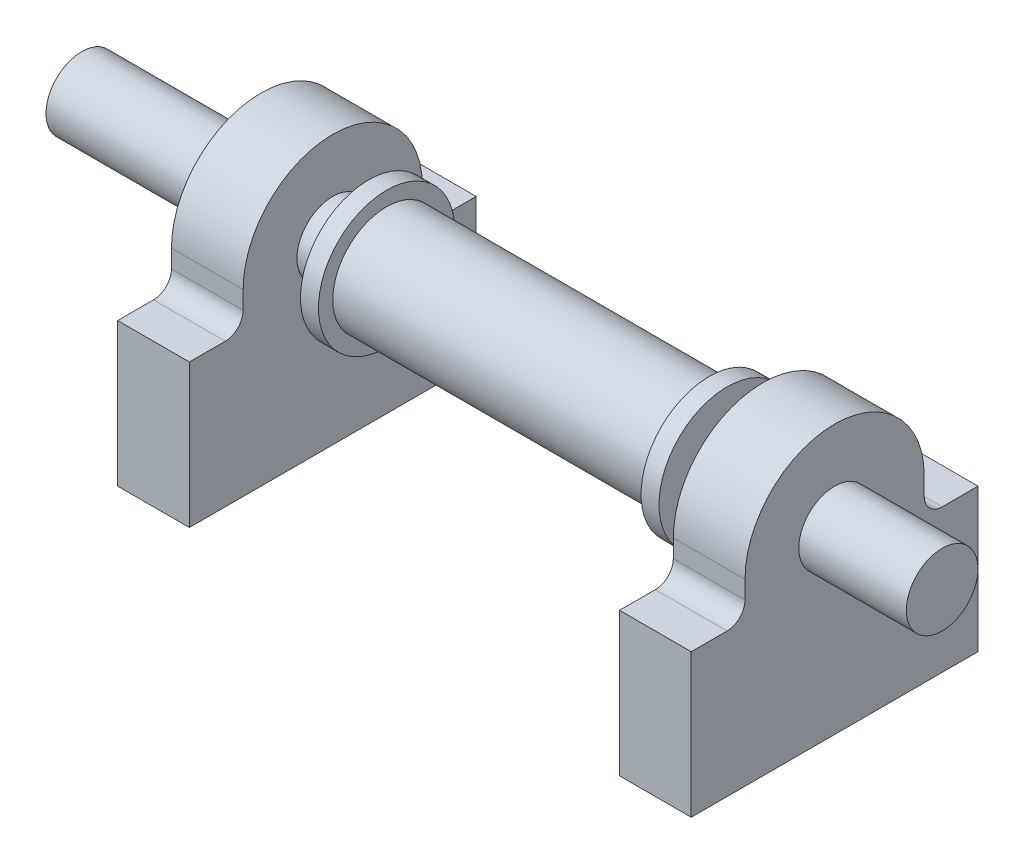
SolidWorks part; units mm, degrees
ref_plane "Front Plane" through (0, 0, 0) normal (0, 0, 1) x (1, 0, 0)
ref_plane "Top Plane" through (0, 0, 0) normal (0, 1, 0) x (1, 0, 0)
ref_plane "Right Plane" through (0, 0, 0) normal (1, 0, 0) x (0, 0, -1)
sketch "Sketch1" plane through (0, 0, 0) normal (0, 1, 0) x (1, 0, 0)
  line L0 (0, 49.2373) -> (0, -47.0339) construction
  line L1 (-87.6271, 0) -> (78.8136, 0) construction
  line L2 (80, -40) -> (60, -40)
  line L3 (-80, 40) -> (-60, 40)
  line L4 (-80, 40) -> (-80, -40)
  line L5 (-80, -40) -> (-60, -40)
  line L6 (-60, 40) -> (-60, -40)
  line L7 (-80, 40) -> (-60, -40) construction
  line L8 (-80, -40) -> (-60, 40) construction
  line L9 (60, 40) -> (60, -40)
  line L10 (80, 40) -> (60, 40)
  line L11 (80, 40) -> (80, -40)
  point P5 (-70, 0)
  dimension "D1" = 20
  dimension "D2" = 80
  dimension "D3" = 60
extrude "Boss-Extrude1" add sketch "Sketch1" along normal blind 40
sketch "Sketch2" plane through (-80, 0, 0) normal (-1, 0, 0) x (0, 0, 1)
  line L0 (-25, 50) -> (-25, 40)
  line L1 (-40, 40) -> (40, 40) construction
  line L3 (25, 40) -> (25, 50)
  line L5 (-25, 40) -> (25, 40)
  line L6 (-40, 40) -> (-40, 0) construction
  arc A0 (25, 50) -> (-25, 50) centre (0, 50) ccw
  dimension "D1" = 25
  dimension "D2" = 40
  dimension "D3" = 10
extrude "Boss-Extrude2" add sketch "Sketch2" against normal up to vertex
sketch "Sketch4" plane through (80, 0, 0) normal (1, 0, 0) x (0, 0, -1)
  line L0 (-25, 50) -> (-25, 40)
  line L1 (-40, 40) -> (40, 40) construction
  line L2 (-25, 40) -> (25, 40)
  line L3 (25, 40) -> (25, 50)
  arc A0 (25, 50) -> (-25, 50) centre (0, 50) ccw
extrude "Boss-Extrude3" add sketch "Sketch4" against normal up to vertex
sketch "Sketch5" plane through (-80, 0, 0) normal (-1, 0, 0) x (0, 0, 1)
  circle A0 centre (0, 50) radius 10
  dimension "D1" = 20
extrude "Cut-Extrude2" cut sketch "Sketch5" against normal blind 170
fillet "Fillet2" radius 5 2 edges at (-70, 40, -25) (-70, 40, 25)
fillet "Fillet3" radius 5 2 edges at (70, 40, -25) (70, 40, 25)
sketch "Sketch6" plane through (-80, 0, 0) normal (-1, 0, 0) x (0, 0, 1)
  circle A0 centre (0, 50) radius 10
  dimension "D1" = 20
extrude "Boss-Extrude4" add sketch "Sketch6" along normal blind 50 and the other way blind 190
ref_plane "Plane2" through (-50, 0, 0) normal (1, 0, 0) x (0, 0, -1)
sketch "Sketch10" plane through (-50, 0, 0) normal (1, 0, 0) x (0, 0, -1)
  circle A0 centre (0, 50) radius 19
  dimension "D1" = 38
extrude "Boss-Extrude6" add sketch "Sketch10" along normal blind 5
mirror "Mirror9" about plane through (0, 0, 0) normal (1, 0, 0) of "Boss-Extrude6"
sketch "Sketch11" plane through (-50, 0, 0) normal (1, 0, 0) x (0, 0, -1)
  circle A0 centre (0, 50) radius 15
  dimension "D1" = 30
extrude "Boss-Extrude7" add sketch "Sketch11" along normal blind 100
